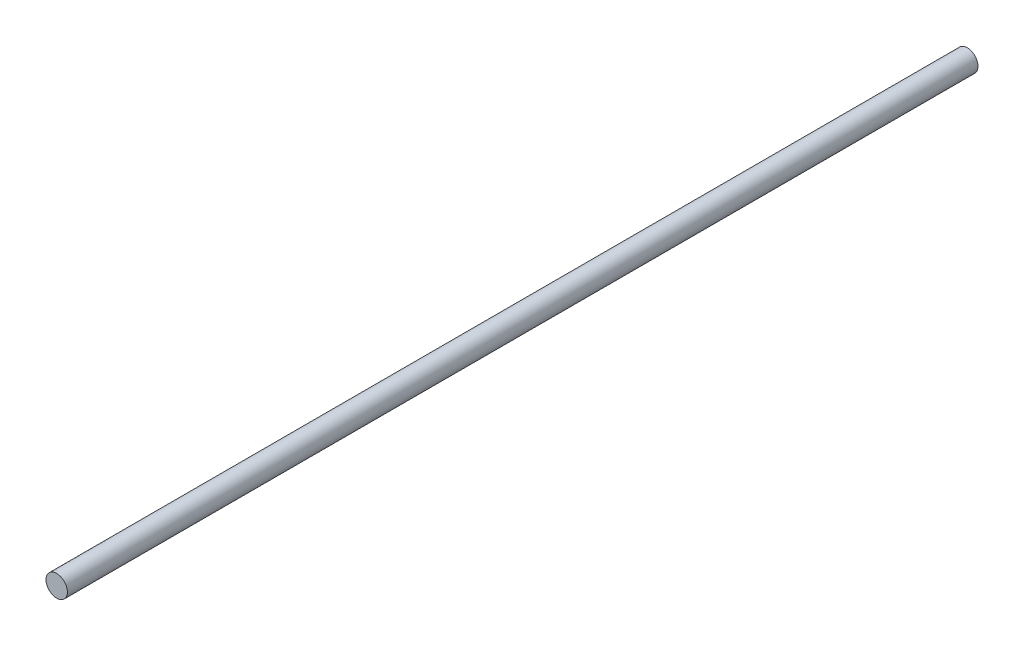
SolidWorks part; units mm, degrees
ref_plane "Front" through (0, 0, 0) normal (0, 0, 1) x (1, 0, 0)
ref_plane "Top" through (0, 0, 0) normal (0, 1, 0) x (1, 0, 0)
ref_plane "Right" through (0, 0, 0) normal (1, 0, 0) x (0, 0, -1)
sketch "Sketch1" plane through (0, 0, 0) normal (0, 0, 1) x (1, 0, 0)
  circle A0 centre (0, 0) radius 4
  dimension "D1" = 8
extrude "Boss-Extrude1" add sketch "Sketch1" along normal blind 339.6
equation "\"linear-bar-dia\"= 8mm ' Diameter of the metal slide bar used on the X Axis"
equation "\"material-thickness\"= 12.4mm"
equation "\"baseplate-width\"= 290mm"
equation "\"D1@Boss-Extrude1\"= \"baseplate-width\" + ( \"material-thickness\" * 4 )"
equation "\"D1@Sketch1\"=\"linear-bar-dia\""
